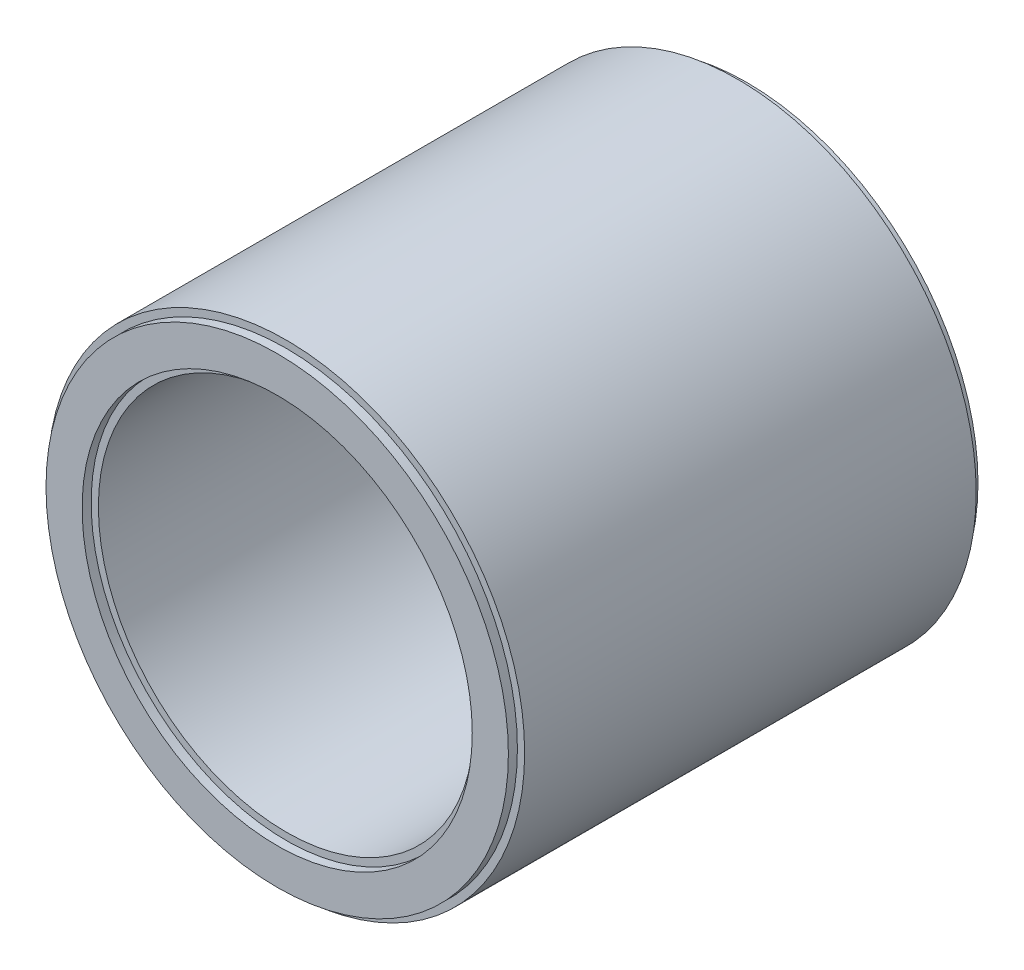
SolidWorks part; units mm, degrees
ref_plane "Plan de face" through (0, 0, 0) normal (0, 0, 1) x (1, 0, 0)
ref_plane "Plan de dessus" through (0, 0, 0) normal (0, 1, 0) x (1, 0, 0)
ref_plane "Plan de droite" through (0, 0, 0) normal (1, 0, 0) x (0, 0, -1)
sketch "Esquisse2" plane through (0, 0, 0) normal (1, 0, 0) x (0, 0, -1)
  line L12 (-6.5, 6.4) -> (-6.25, 6.4)
  line L13 (-6.25, 6.4) -> (-6.25, 6.6)
  line L14 (-6.25, 6.6) -> (6.25, 6.6)
  line L15 (6.25, 6.6) -> (6.25, 6.4)
  line L16 (6.25, 6.4) -> (6.5, 6.4)
  line L17 (6.5, 6.4) -> (6.5, 5.4)
  line L18 (6.5, 5.4) -> (6.25, 5.4)
  line L19 (6.25, 5.4) -> (6.25, 5.2)
  line L20 (6.25, 5.2) -> (-6.25, 5.2)
  line L21 (-6.25, 5.2) -> (-6.25, 5.4)
  line L22 (-6.25, 5.4) -> (-6.5, 5.4)
  line L23 (-6.5, 5.4) -> (-6.5, 6.4)
  line L24 (-6.8836, 0) -> (6.5, 0) construction
  point P17 (0, 5.2)
  dimension "D1" = 6.6
  dimension "D2" = 5.2
  dimension "D3" = 13
  dimension "D4" = 12.5
  dimension "D5" = 1
revolve "Révolution1" add sketch "Esquisse2" angle 360 about L24
